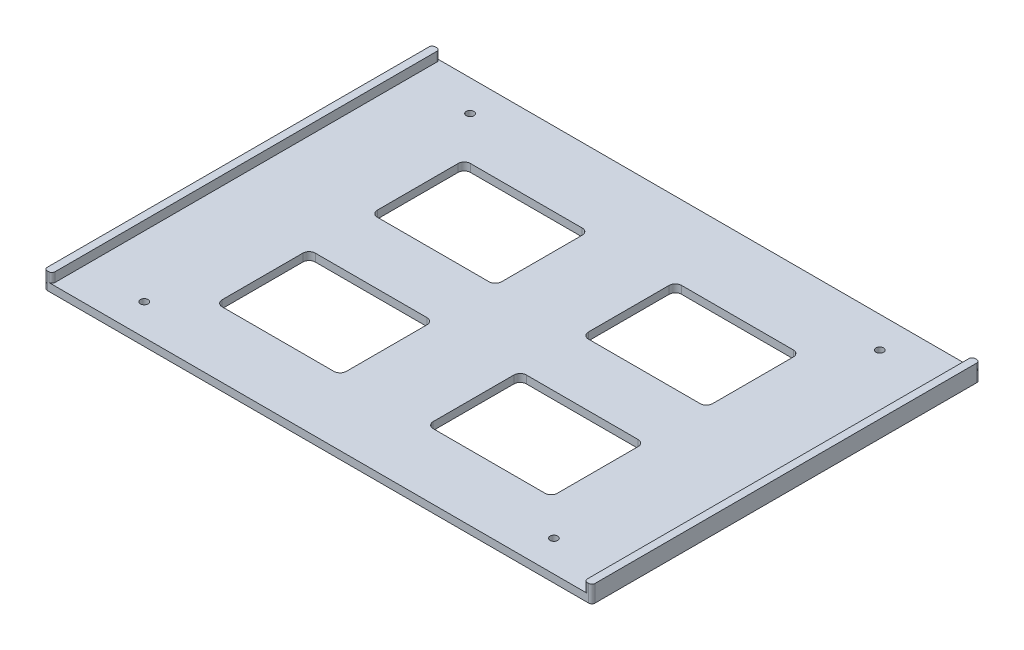
SolidWorks part; units mm, degrees
ref_plane "Front Plane" through (0, 0, 0) normal (0, 0, 1) x (1, 0, 0)
ref_plane "Top Plane" through (0, 0, 0) normal (0, 1, 0) x (1, 0, 0)
ref_plane "Right Plane" through (0, 0, 0) normal (1, 0, 0) x (0, 0, -1)
sketch "Sketch1" plane through (0, 0, 0) normal (0, 1, 0) x (1, 0, 0)
  line L1 (0, 0) -> (171.45, 0)
  line L2 (0, 0) -> (0, -125)
  line L3 (0, -125) -> (171.45, -125)
  line L4 (171.45, 0) -> (171.45, -125)
  line L5 (0, 0) -> (171.45, -125) construction
  line L6 (0, -125) -> (171.45, 0) construction
  line L7 (19.725, -115) -> (151.725, -115) construction
  line L8 (19.725, -115) -> (19.725, -10) construction
  line L9 (19.725, -10) -> (151.725, -10) construction
  line L10 (151.725, -115) -> (151.725, -10) construction
  line L11 (19.725, -115) -> (151.725, -10) construction
  line L12 (19.725, -10) -> (151.725, -115) construction
  circle A0 centre (19.725, -10) radius 1.23
  circle A1 centre (151.725, -10) radius 1.23
  circle A2 centre (19.725, -115) radius 1.23
  circle A3 centre (151.725, -115) radius 1.23
  point P4 (85.725, -62.5)
  point P10 (85.725, -62.5)
  dimension "D5" = 2.46
  dimension "D6" = 2.46
  dimension "D7" = 2.46
  dimension "D8" = 2.46
  dimension "D1" = 171.45
  dimension "D2" = 125
  dimension "D3" = 132
  dimension "D4" = 105
extrude "Boss-Extrude1" add sketch "Sketch1" along normal blind 2.5
sketch "Sketch2" plane through (0, 2.5, 0) normal (0, 1, 0) x (1, 0, 0)
  line L0 (0, -125) -> (171.45, -125) construction
  line L1 (0, 0) -> (-2.5, 0)
  line L2 (0, 0) -> (0, -125)
  line L3 (0, -125) -> (-2.5, -125)
  line L4 (-2.5, 0) -> (-2.5, -125)
  line L5 (0, 0) -> (-2.5, -125) construction
  line L6 (0, -125) -> (-2.5, 0) construction
  line L7 (171.45, -125) -> (173.95, -125)
  line L8 (171.45, -125) -> (171.45, 0)
  line L9 (171.45, 0) -> (173.95, 0)
  line L10 (173.95, -125) -> (173.95, 0)
  line L11 (171.45, -125) -> (173.95, 0) construction
  line L12 (171.45, 0) -> (173.95, -125) construction
  line L13 (171.45, 0) -> (0, 0) construction
  point P4 (-1.25, -62.5)
  point P10 (172.7, -62.5)
  dimension "D1" = 2.5
  dimension "D2" = 2.5
extrude "Boss-Extrude2" add sketch "Sketch2" along normal blind 3 and the other way up to surface (2.5 mm away) other way up to face at (85.725, 0, 62.5)
sketch "Sketch3" plane through (0, 2.5, 0) normal (0, 1, 0) x (1, 0, 0)
  line L0 (51.725, 0) -> (51.725, -125) construction
  line L1 (31.725, -23.877) -> (71.725, -23.877)
  line L2 (31.725, -23.877) -> (31.725, -53.877)
  line L3 (31.725, -53.877) -> (71.725, -53.877)
  line L4 (71.725, -23.877) -> (71.725, -53.877)
  line L5 (31.725, -23.877) -> (71.725, -53.877) construction
  line L6 (31.725, -53.877) -> (71.725, -23.877) construction
  line L7 (139.725, -23.877) -> (99.725, -23.877)
  line L8 (139.725, -23.877) -> (139.725, -53.877)
  line L9 (139.725, -53.877) -> (99.725, -53.877)
  line L10 (99.725, -23.877) -> (99.725, -53.877)
  line L11 (139.725, -23.877) -> (99.725, -53.877) construction
  line L12 (139.725, -53.877) -> (99.725, -23.877) construction
  line L13 (31.725, -73.877) -> (71.725, -73.877)
  line L14 (31.725, -73.877) -> (31.725, -103.877)
  line L15 (31.725, -103.877) -> (71.725, -103.877)
  line L16 (71.725, -73.877) -> (71.725, -103.877)
  line L17 (31.725, -73.877) -> (71.725, -103.877) construction
  line L18 (31.725, -103.877) -> (71.725, -73.877) construction
  line L19 (99.725, -73.877) -> (139.725, -73.877)
  line L20 (99.725, -73.877) -> (99.725, -103.877)
  line L21 (99.725, -103.877) -> (139.725, -103.877)
  line L22 (139.725, -73.877) -> (139.725, -103.877)
  line L23 (99.725, -73.877) -> (139.725, -103.877) construction
  line L24 (99.725, -103.877) -> (139.725, -73.877) construction
  line L25 (171.45, 0) -> (0, 0) construction
  line L26 (0, -125) -> (171.45, -125) construction
  line L27 (119.725, -125) -> (119.725, 0) construction
  circle A1 centre (151.725, -10) radius 1.23 construction
  circle A2 centre (19.725, -10) radius 1.23 construction
  point P4 (51.725, -38.877)
  point P9 (119.725, -38.877)
  point P14 (51.725, -88.877)
  point P19 (119.725, -88.877)
  point P28 (125.8562, -36.249)
  point P29 (125.8562, -85.0335)
  point P30 (46.88, -86.5869)
  point P31 (46.88, -38.2676)
  point P32 (125.2683, -35.1401)
  point P33 (122.565, -34.5394)
  point P34 (0, 0)
  dimension "D1" = 40
  dimension "D2" = 40
  dimension "D3" = 40
  dimension "D4" = 40
  dimension "D5" = 30
  dimension "D6" = 30
  dimension "D7" = 30
  dimension "D8" = 30
  dimension "D9" = 32
  dimension "D10" = 32
  dimension "D11" = 20
extrude "Cut-Extrude1" cut sketch "Sketch3" against normal through all both and the other way through all
fillet "Fillet1" radius 2 16 edges at (139.725, 1.25, 53.877) (139.725, 1.25, 23.877) (99.725, 1.25, 23.877) (99.725, 1.25, 53.877) (99.725, 1.25, 103.877) (99.725, 1.25, 73.877) (139.725, 1.25, 73.877) (139.725, 1.25, 103.877) (71.725, 1.25, 103.877) (31.725, 1.25, 103.877) (31.725, 1.25, 73.877) (71.725, 1.25, 73.877) (31.725, 1.25, 53.877) (71.725, 1.25, 53.877) (71.725, 1.25, 23.877) (31.725, 1.25, 23.877)
fillet "Fillet2" radius 1 8 edges at (173.95, 2.75, 125) (171.45, 4, 125) (0, 4, 125) (0, 4, 0) (171.45, 4, 0) (173.95, 2.75, 0) (-2.5, 2.75, 0) (-2.5, 2.75, 125)
